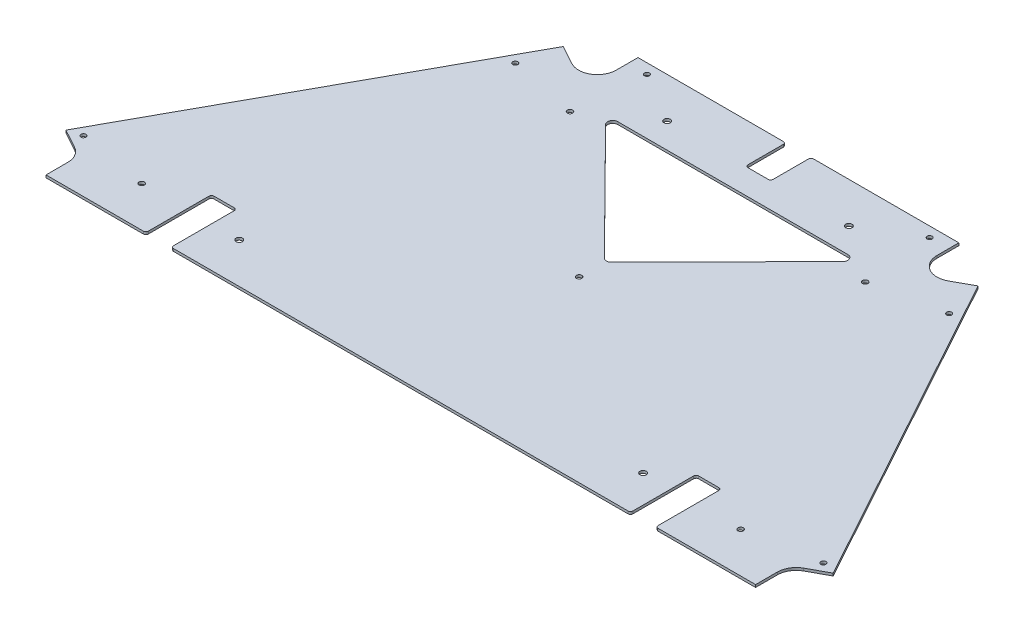
SolidWorks part; units mm, degrees
material "PC High Viscosity"
ref_plane "Front Plane" through (0, 0, 0) normal (0, 0, 1) x (1, 0, 0)
ref_plane "Top Plane" through (0, 0, 0) normal (0, 1, 0) x (1, 0, 0)
ref_plane "Right Plane" through (0, 0, 0) normal (1, 0, 0) x (0, 0, -1)
sketch "Sketch1" plane through (0, 0, 0) normal (0, 1, 0) x (1, 0, 0)
  line L0 (-505.5243, 6.35) -> (-237.901, 493.8184) construction
  line L1 (-237.901, 493.8184) -> (237.901, 493.8184) construction
  line L2 (237.901, 493.8184) -> (505.5243, 6.35) construction
  line L3 (505.5243, 6.35) -> (-505.5243, 6.35) construction
  line L4 (-516.2546, 0) -> (-241.6589, 500.1684)
  line L5 (-241.6589, 500.1684) -> (241.6589, 500.1684)
  line L6 (241.6589, 500.1684) -> (516.2546, 0)
  line L7 (516.2546, 0) -> (-516.2546, 0)
  line L8 (-201.803, 472.7364) -> (-201.803, 500.1684)
  line L9 (-236.7931, 452.0297) -> (-260.8395, 465.2314)
  line L10 (-458.5319, 48.1387) -> (-482.5783, 61.3403)
  line L11 (-446.278, 27.432) -> (-446.278, 0)
  line L12 (0, 500.1684) -> (0, 0) construction
  line L13 (446.278, 27.432) -> (446.278, 0)
  line L14 (458.5319, 48.1387) -> (482.5783, 61.3403)
  line L15 (236.7931, 452.0297) -> (260.8395, 465.2314)
  line L16 (201.803, 472.7364) -> (201.803, 500.1684)
  circle A0 centre (-225.425, 472.7364) radius 21.082 construction
  circle A1 centre (225.425, 472.7364) radius 21.082 construction
  circle A2 centre (469.9, 27.432) radius 21.082 construction
  circle A3 centre (-469.9, 27.432) radius 21.082 construction
  circle A4 centre (-225.425, 472.7364) radius 23.622 construction
  circle A5 centre (-469.9, 27.432) radius 23.622 construction
  arc A6 (-458.5319, 48.1387) -> (-446.278, 27.432) centre (-469.9, 27.432) cw
  arc A7 (-236.7931, 452.0297) -> (-201.803, 472.7364) centre (-225.425, 472.7364) ccw
  arc A8 (458.5319, 48.1387) -> (446.278, 27.432) centre (469.9, 27.432) ccw
  arc A9 (236.7931, 452.0297) -> (201.803, 472.7364) centre (225.425, 472.7364) cw
  point P27 (0, 0)
  dimension "D1" = 42.164
  dimension "D2" = 450.85
  dimension "D3" = 508
  dimension "D4" = 939.8
  dimension "D6" = 6.35
  dimension "D7" = 2.54
extrude "Boss-Extrude1" add sketch "Sketch1" along normal blind 3.175 contours L15 A9 L16 L5 L8 A7 L9 L4 L10 A6 L11 L7 L13 A8 L14 L6
sketch "Sketch2" plane through (0, 3.175, 0) normal (0, 1, 0) x (1, 0, 0)
  line L0 (446.278, 0) -> (-446.278, 0) construction
  line L1 (-288.925, 0) -> (-320.675, 0)
  line L2 (-288.925, 0) -> (-288.925, 82.55)
  line L3 (-288.925, 82.55) -> (-320.675, 82.55)
  line L4 (-320.675, 0) -> (-320.675, 82.55)
  line L5 (0, 0) -> (0, 500.1684) construction
  line L6 (-201.803, 500.1684) -> (201.803, 500.1684) construction
  line L7 (288.925, 82.55) -> (320.675, 82.55)
  line L8 (320.675, 0) -> (320.675, 82.55)
  line L9 (288.925, 0) -> (320.675, 0)
  line L10 (288.925, 0) -> (288.925, 82.55)
  point P11 (-304.8, 0)
  dimension "D1" = 31.75
  dimension "D2" = 82.55
  dimension "D3" = 304.8
extrude "Cut-Extrude1" cut sketch "Sketch2" against normal through all
fillet "Fillet1" radius 3.175 8 edges at (288.925, 1.5875, -82.55) (288.925, 1.5875, 0) (320.675, 1.5875, -82.55) (320.675, 1.5875, 0) (-288.925, 1.5875, 0) (-288.925, 1.5875, -82.55) (-320.675, 1.5875, -82.55) (-320.675, 1.5875, 0)
hole_wizard "1/4 (0.25) Diameter Hole1" positions "Sketch5" profile "Sketch6" hole size "1/4" standard "ANSI Inch" end condition through all
sketch "Sketch5" plane through (0, 3.175, 0) normal (0, 1, 0) x (1, 0, 0)
  line L0 (0, 0) -> (0, 500.1684)
  line L1 (-201.803, 500.1684) -> (201.803, 500.1684) construction
  line L3 (-482.5783, 61.3403) -> (-260.8395, 465.2314) construction
  line L4 (-446.278, 0) -> (-516.2546, 0) construction
  line L5 (-516.2546, 0) -> (-482.5783, 61.3403) construction
  line L7 (-465.3948, 66.2501) -> (-476.5274, 72.362) construction
  line L9 (-272.8707, 416.9273) -> (-284.0033, 423.0391) construction
  point P0 (-465.3948, 66.2501)
  point P2 (-272.8707, 416.9273)
  point P4 (-177.8, 487.4684)
  point P38 (465.3948, 66.2501)
  point P39 (272.8707, 416.9273)
  point P40 (177.8, 487.4684)
  dimension "D1" = 12.7
  dimension "D2" = 177.8
  dimension "D3" = 12.7
  dimension "D4" = 12.7
  dimension "D5" = 82.55
  dimension "D6" = 482.6
sketch "Sketch6" plane through (-465.3948, 3.175, -66.2501) normal (1, 0, 0) x (0, 0, 1)
  line L0 (0, 0) -> (0, 3.175)
  line L1 (0, 3.175) -> (3.175, 3.175)
  line L2 (3.175, 3.175) -> (3.175, 0)
  line L5 (3.175, 0) -> (0, 0)
  line L11 (0, -6.35) -> (0, 107.95) construction
  dimension "Thru Hole Dia." = 6.35
  dimension "Thru Hole Depth" = 3.175
hole_wizard "1/4 Clearance Hole1" positions "Sketch7" profile "Sketch8" hole size "1/4" standard "ANSI Inch" end condition through all
sketch "Sketch7" plane through (0, 3.175, 0) normal (0, 1, 0) x (1, 0, 0)
  line L0 (0, 0) -> (0, 500.1684) construction
  line L1 (-201.803, 500.1684) -> (201.803, 500.1684) construction
  line L2 (-323.85, 0) -> (-446.278, 0) construction
  line L3 (285.75, 0) -> (-285.75, 0) construction
  point P7 (-376.682, 50.8)
  point P9 (-185.674, 398.526)
  point P16 (376.682, 50.8)
  point P17 (185.674, 398.526)
  point P18 (0, 224.282)
  dimension "D1" = 50.8
  dimension "D2" = 376.682
  dimension "D3" = 398.526
  dimension "D4" = 185.674
  dimension "D5" = 224.282
sketch "Sketch8" plane through (0, 3.175, -224.282) normal (1, 0, 0) x (0, 0, 1)
  line L0 (0, 0) -> (0, 3.175)
  line L1 (0, 3.175) -> (3.3782, 3.175)
  line L2 (3.3782, 3.175) -> (3.3782, 0)
  line L5 (3.3782, 0) -> (0, 0)
  line L11 (0, -6.35) -> (0, 107.95) construction
  dimension "Thru Hole Dia." = 6.7564
  dimension "Thru Hole Depth" = 3.175
hole_wizard "5/16 (0.3125) Diameter Hole1" positions "Sketch9" profile "Sketch10" hole size "5/16" standard "ANSI Inch" end condition through all
sketch "Sketch9" plane through (0, 3.175, 0) normal (0, 1, 0) x (1, 0, 0)
  line L0 (0, 0) -> (0, 500.1684) construction
  line L1 (-201.803, 500.1684) -> (201.803, 500.1684) construction
  line L3 (285.75, 0) -> (-285.75, 0) construction
  point P0 (-254, 50.8)
  point P2 (-114.3, 449.3684)
  point P13 (254, 50.8)
  point P14 (114.3, 449.3684)
  dimension "D1" = 50.8
  dimension "D2" = 254
  dimension "D3" = 50.8
  dimension "D4" = 114.3
sketch "Sketch10" plane through (-254, 3.175, -50.8) normal (1, 0, 0) x (0, 0, 1)
  line L0 (0, 0) -> (0, 3.175)
  line L1 (0, 3.175) -> (3.9687, 3.175)
  line L2 (3.9687, 3.175) -> (3.9687, 0)
  line L5 (3.9687, 0) -> (0, 0)
  line L11 (0, -6.35) -> (0, 107.95) construction
  dimension "Thru Hole Dia." = 7.9375
  dimension "Thru Hole Depth" = 3.175
sketch "Sketch11" plane through (0, 3.175, 0) normal (0, 1, 0) x (1, 0, 0)
  line L0 (0, 256.032) -> (159.8995, 417.6184)
  line L1 (159.8995, 417.6184) -> (-159.8995, 417.6184)
  line L2 (-159.8995, 417.6184) -> (0, 256.032)
  circle A0 centre (0, 224.282) radius 3.3782 construction
  circle A1 centre (-114.3, 449.3684) radius 3.9687 construction
  circle A2 centre (-185.674, 398.526) radius 3.3782 construction
  dimension "D1" = 31.75
  dimension "D2" = 31.75
  dimension "D3" = 31.75
extrude "Cut-Extrude2" cut sketch "Sketch11" against normal through all
fillet "Fillet2" radius 6.35 3 edges at (0, 1.5875, -256.032) (159.8995, 1.5875, -417.6184) (-159.8995, 1.5875, -417.6184)
sketch "Sketch12" plane through (0, 3.175, 0) normal (0, 1, 0) x (1, 0, 0)
  line L0 (-201.803, 500.1684) -> (201.803, 500.1684) construction
  line L1 (-15.875, 500.1684) -> (15.875, 500.1684)
  line L2 (-15.875, 500.1684) -> (-15.875, 449.3684)
  line L3 (-15.875, 449.3684) -> (15.875, 449.3684)
  line L4 (15.875, 500.1684) -> (15.875, 449.3684)
  point P6 (0, 500.1684)
  dimension "D1" = 50.8
  dimension "D2" = 31.75
extrude "Cut-Extrude3" cut sketch "Sketch12" against normal through all
fillet "Fillet3" radius 3.175 4 edges at (15.875, 1.5875, -449.3684) (15.875, 1.5875, -500.1684) (-15.875, 1.5875, -449.3684) (-15.875, 1.5875, -500.1684)
